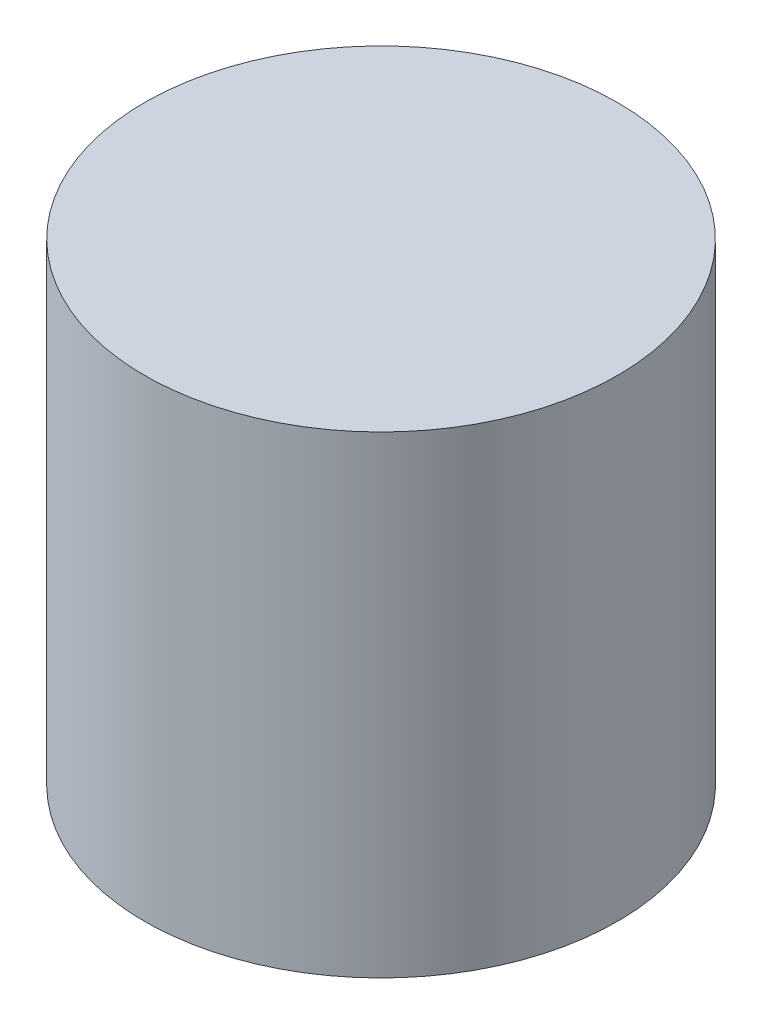
SolidWorks part; units mm, degrees
ref_plane "前视基准面" through (0, 0, 0) normal (0, 0, 1) x (1, 0, 0)
ref_plane "上视基准面" through (0, 0, 0) normal (0, 1, 0) x (1, 0, 0)
ref_plane "右视基准面" through (0, 0, 0) normal (1, 0, 0) x (0, 0, -1)
sketch "草图1" plane through (0, 0, 0) normal (0, 1, 0) x (1, 0, 0)
  circle A0 centre (0, 0) radius 50
extrude "凸台-拉伸1" add sketch "草图1" along normal blind 100
